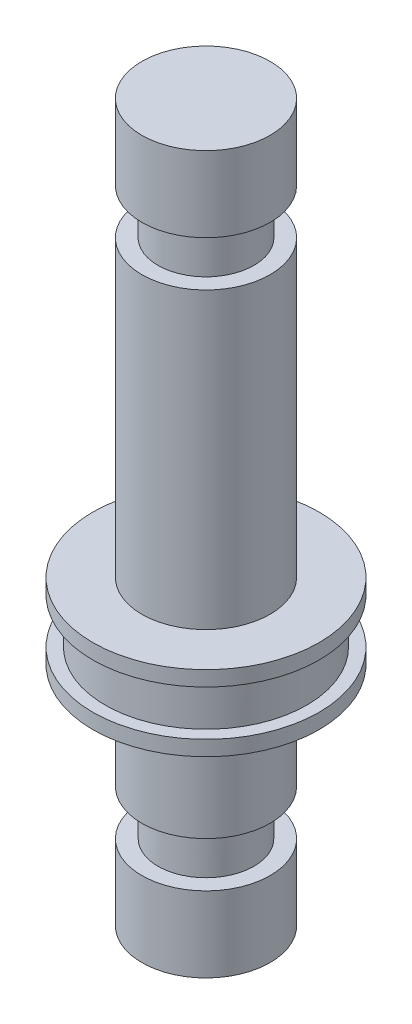
SolidWorks part; units mm, degrees
ref_plane "Front Plane" through (0, 0, 0) normal (0, 0, 1) x (1, 0, 0)
ref_plane "Top Plane" through (0, 0, 0) normal (0, 1, 0) x (1, 0, 0)
ref_plane "Right Plane" through (0, 0, 0) normal (1, 0, 0) x (0, 0, -1)
sketch "Sketch1" plane through (0, 0, 0) normal (0, 1, 0) x (1, 0, 0)
  circle A0 centre (0, 0) radius 13.365
  dimension "D1" = 26.73
extrude "Boss-Extrude1" add sketch "Sketch1" along normal blind 10
sketch "Sketch2" plane through (0, 10, 0) normal (0, 1, 0) x (1, 0, 0)
  circle A0 centre (0, 0) radius 15
  dimension "D1" = 30
extrude "Boss-Extrude2" add sketch "Sketch2" against normal blind 2
sketch "Sketch3" plane through (0, 0, 0) normal (0, -1, 0) x (1, 0, 0)
  circle A0 centre (0, 0) radius 15
  dimension "D1" = 30
extrude "Boss-Extrude3" add sketch "Sketch3" against normal blind 2
sketch "Sketch4" plane through (0, 0, 0) normal (0, -1, 0) x (1, 0, 0)
  circle A0 centre (0, 0) radius 6.365
  dimension "D1" = 12.73
extrude "Boss-Extrude4" add sketch "Sketch4" along normal blind 30 and the other way blind 65
sketch "Sketch5" plane through (0, -30, 0) normal (0, -1, 0) x (1, 0, 0)
  circle A0 centre (0, 0) radius 8.5
  dimension "D1" = 17
extrude "Boss-Extrude5" add sketch "Sketch5" against normal blind 10
sketch "Sketch6" plane through (0, 65, 0) normal (0, 1, 0) x (1, 0, 0)
  circle A0 centre (0, 0) radius 8.5
  dimension "D1" = 17
extrude "Boss-Extrude6" add sketch "Sketch6" against normal blind 10
ref_plane "Plane1" through (0, -14, 0) normal (0, 1, 0) x (1, 0, 0)
sketch "Sketch7" plane through (0, -14, 0) normal (0, 1, 0) x (1, 0, 0)
  circle A0 centre (0, 0) radius 8.5
  dimension "D1" = 17
extrude "Boss-Extrude7" add sketch "Sketch7" along normal offset from surface (63 mm away) 6 up to face at (0, 55, 6.365)
